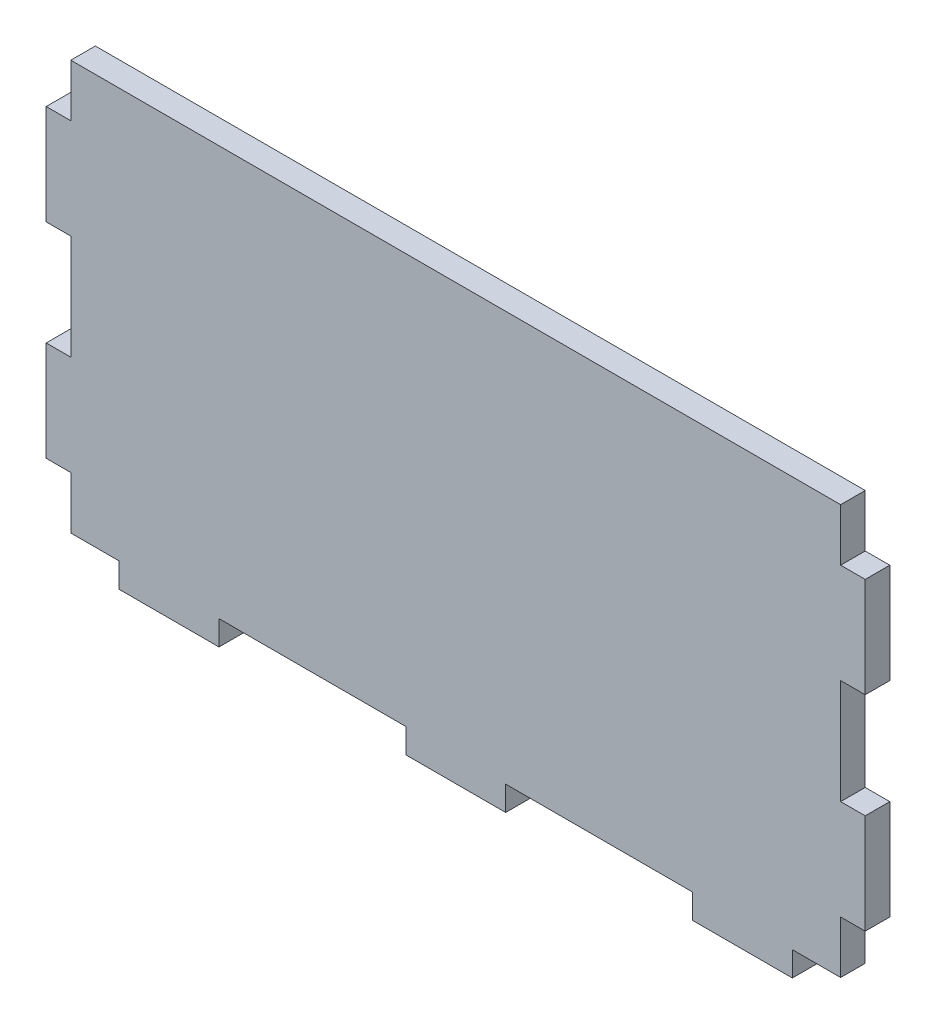
SolidWorks part; units mm, degrees
ref_plane "Спереди" through (0, 0, 0) normal (0, 0, 1) x (1, 0, 0)
ref_plane "Сверху" through (0, 0, 0) normal (0, 1, 0) x (1, 0, 0)
ref_plane "Справа" through (0, 0, 0) normal (1, 0, 0) x (0, 0, -1)
sketch "Эскиз1" plane through (0, 0, 0) normal (0, 0, 1) x (1, 0, 0)
  line L0 (47, 50) -> (47, 0) construction
  line L1 (0, 0) -> (5.9, 0)
  line L2 (0, 0) -> (0, 6.4)
  line L3 (0, 50) -> (94, 50)
  line L4 (94, 0) -> (94, 6.4)
  line L5 (47, 25) -> (0, 25) construction
  line L6 (-3, 37.5) -> (47, 37.5) construction
  line L7 (0, 43.6) -> (-3, 43.6)
  line L9 (0, 31.4) -> (-3, 31.4)
  line L10 (-3, 43.6) -> (-3, 31.4)
  line L23 (0, 43.6) -> (0, 50)
  line L24 (0, 18.6) -> (0, 31.4)
  line L25 (94, 43.6) -> (94, 50)
  line L26 (94, 18.6) -> (94, 31.4)
  line L27 (-3, 31.4) -> (-3, 18.6) construction
  line L28 (0, 18.6) -> (-3, 18.6)
  line L29 (-3, 6.4) -> (-3, 18.6)
  line L30 (0, 6.4) -> (-3, 6.4)
  line L31 (94, 6.4) -> (97, 6.4)
  line L32 (97, 6.4) -> (97, 18.6)
  line L33 (94, 18.6) -> (97, 18.6)
  line L34 (94, 31.4) -> (97, 31.4)
  line L35 (97, 43.6) -> (97, 31.4)
  line L36 (94, 43.6) -> (97, 43.6)
  line L37 (40.9, 0) -> (40.9, -3)
  line L38 (40.9, -3) -> (53.1, -3)
  line L39 (53.1, 0) -> (75.9, 0)
  line L40 (53.1, 0) -> (53.1, -3)
  line L41 (75.9, -3) -> (88.1, -3)
  line L42 (75.9, 0) -> (75.9, -3)
  line L43 (88.1, 0) -> (88.1, -3)
  line L44 (18.1, 0) -> (18.1, -3)
  line L45 (5.9, 0) -> (5.9, -3)
  line L46 (18.1, -3) -> (5.9, -3)
  line L47 (18.1, 0) -> (40.9, 0)
  line L48 (88.1, 0) -> (94, 0)
  line L49 (82, -3) -> (82, 6.7371) construction
  line L50 (53.1, 0) -> (40.9, 0) construction
  point P6 (47, 25)
  point P32 (47, -3)
  dimension "D1" = 94
  dimension "D2" = 50
  dimension "D3" = 12.5
  dimension "D4" = 3
  dimension "D5" = 12.2
  dimension "D6" = 12.2
  dimension "D7" = 3
  dimension "D9" = 35
  dimension "D8" = 2
extrude "Бобышка-Вытянуть1" add sketch "Эскиз1" against normal blind 3
